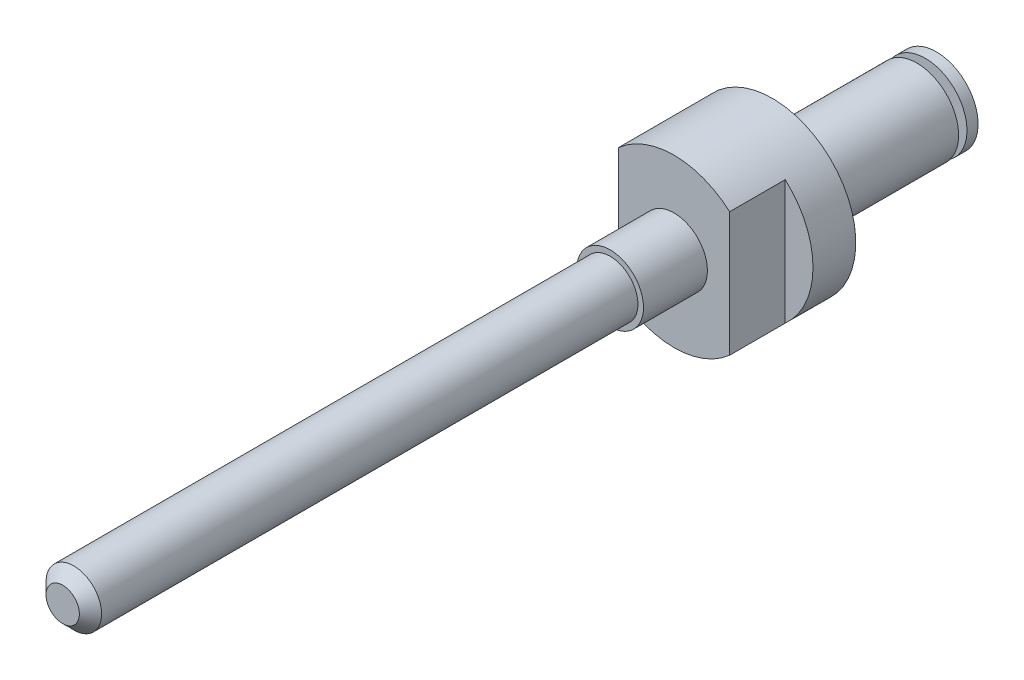
SolidWorks part; units mm, degrees
material "Cast Alloy Steel"
ref_plane "Front Plane" through (0, 0, 0) normal (0, 0, 1) x (1, 0, 0)
ref_plane "Top Plane" through (0, 0, 0) normal (0, 1, 0) x (1, 0, 0)
ref_plane "Right Plane" through (0, 0, 0) normal (1, 0, 0) x (0, 0, -1)
sketch "Sketch1" plane through (0, 0, 0) normal (0, 1, 0) x (1, 0, 0)
  line L0 (0, 0) -> (-1.5, 0)
  line L1 (-1.5, 0) -> (-1.5, 1.77)
  line L2 (-1.5, 1.77) -> (-0.75, 1.77)
  line L3 (-0.75, 1.77) -> (-0.75, 4.37)
  line L4 (-0.75, 4.37) -> (-0.5, 4.37)
  line L5 (-0.5, 4.37) -> (-0.5, 4.52)
  line L6 (-0.5, 4.52) -> (-0.75, 4.52)
  line L7 (-0.75, 4.52) -> (-0.75, 4.72)
  line L8 (-0.75, 4.72) -> (0, 4.72)
  line L9 (0, 4.72) -> (0, 0)
  dimension "D1" = 1.5
  dimension "D2" = 1.77
  dimension "D3" = 0.2
  dimension "D4" = 4.72
  dimension "D5" = 4.37
  dimension "D6" = 0.75
  dimension "D7" = 0.25
revolve "Revolve1" add sketch "Sketch1" angle 360 about L9
sketch "Sketch2" plane through (0, 0, 0) normal (0, 0, 1) x (1, 0, 0)
  line L0 (0, 1.5) -> (0, -1.5) construction
  line L1 (-2, 1.5) -> (-1, 1.5)
  line L2 (-2, 1.5) -> (-2, -1.5)
  line L3 (-2, -1.5) -> (-1, -1.5)
  line L4 (-1, 1.5) -> (-1, -1.5)
  line L5 (-2, 1.5) -> (-1, -1.5) construction
  line L6 (-2, -1.5) -> (-1, 1.5) construction
  line L7 (1, 1.5) -> (2, 1.5)
  line L8 (1, 1.5) -> (1, -1.5)
  line L9 (1, -1.5) -> (2, -1.5)
  line L10 (2, 1.5) -> (2, -1.5)
  line L11 (1, 1.5) -> (2, -1.5) construction
  line L12 (1, -1.5) -> (2, 1.5) construction
  circle A0 centre (0, 0) radius 1.5 construction
  point P0 (-1.5, 0)
  point P5 (1.5, 0)
  point P14 (0, 0)
  dimension "D1" = 3
  dimension "D2" = 1
  dimension "D3" = 1
extrude "Cut-Extrude1" cut sketch "Sketch2" against normal blind 1
sketch "Sketch3" plane through (0, 0, 0) normal (0, 0, 1) x (1, 0, 0)
  circle A0 centre (0, 0) radius 0.6
  dimension "D1" = 1.2
extrude "Boss-Extrude1" add sketch "Sketch3" along normal blind 11
sketch "Sketch4" plane through (0, 0, 0) normal (0, 0, 1) x (1, 0, 0)
  circle A0 centre (0, 0) radius 0.6 construction
  circle A1 centre (0, 0) radius 0.6
  circle A2 centre (0, 0) radius 0.5
  dimension "D1" = 1
extrude "Cut-Extrude2" cut sketch "Sketch4" along normal through all from offset 1.15
chamfer "Chamfer1" distance 0.2 angle 45 1 edges at (0.5, 0, 11)
